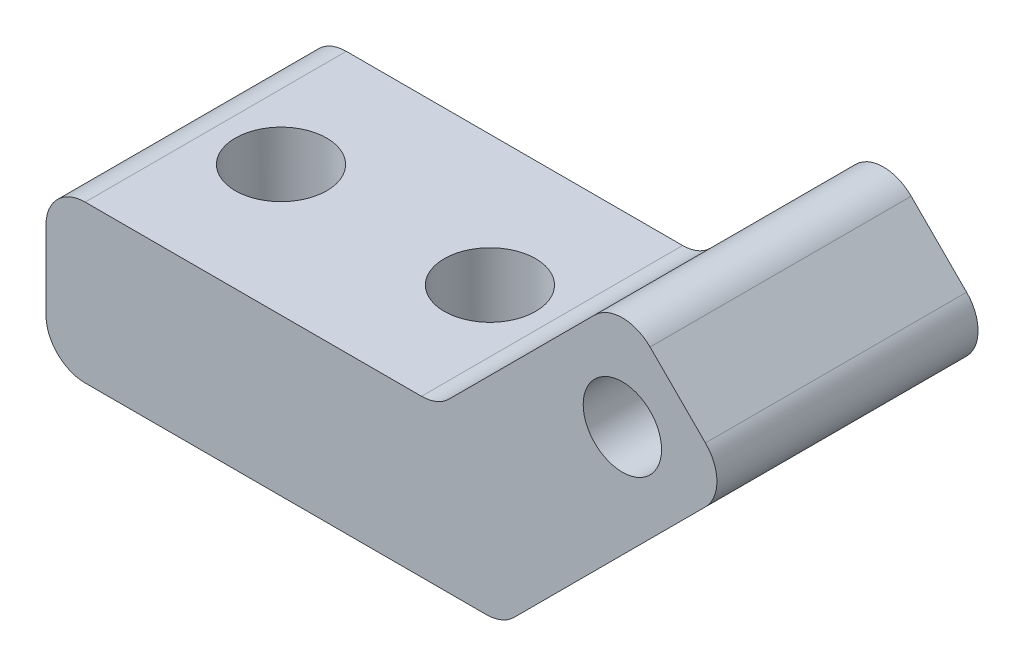
SolidWorks part; units mm, degrees
ref_plane "Front" through (0, 0, 0) normal (0, 0, 1) x (1, 0, 0)
ref_plane "Top" through (0, 0, 0) normal (0, 1, 0) x (1, 0, 0)
ref_plane "Right" through (0, 0, 0) normal (1, 0, 0) x (0, 0, -1)
sketch "Esquisse1" plane through (0, 0, 0) normal (0, 0, 1) x (1, 0, 0)
  line L1 (0, 0) -> (30, 0)
  line L2 (0, 0) -> (0, 12)
  line L3 (0, 12) -> (30, 12)
  line L4 (30, 0) -> (30, 12)
  dimension "D1" = 30
  dimension "D2" = 12
extrude "Boss.-Extru.1" add sketch "Esquisse1" along normal blind 20
sketch "Esquisse2" plane through (0, 0, 20) normal (0, 0, 1) x (1, 0, 0)
  line L0 (30, 0) -> (34.9706, 0)
  line L1 (34.9706, 0) -> (52.6274, 17.6569)
  line L2 (52.6274, 17.6569) -> (44.1421, 26.1421)
  line L3 (44.1421, 26.1421) -> (30, 12)
  line L4 (30, 12) -> (30, 0)
  line L5 (30, 12) -> (0, 12) construction
  dimension "D1" = 135
  dimension "D2" = 12
  dimension "D3" = 20
extrude "Boss.-Extru.2" add sketch "Esquisse2" against normal up to vertex (20 mm away)
sketch "Esquisse3" plane through (0, 12, 0) normal (0, 1, 0) x (1, 0, 0)
  line L0 (0, -10) -> (30, -10) construction
  line L1 (0, -20) -> (0, 0) construction
  line L2 (30, -20) -> (30, 0) construction
  circle A0 centre (8, -10) radius 3.5
  circle A1 centre (24, -10) radius 3.5
  dimension "D1" = 16
  dimension "D2" = 8
  dimension "D3" = 7
extrude "Enlèv. mat.-Extru.1" cut sketch "Esquisse3" against normal through all both and the other way through all
sketch "Esquisse4" plane through (0, 0, 20) normal (0, 0, 1) x (1, 0, 0)
  line L0 (48.3848, 21.8995) -> (44.1421, 17.6569) construction
  line L1 (52.6274, 17.6569) -> (44.1421, 26.1421) construction
  circle A0 centre (44.1421, 17.6569) radius 3
  dimension "D1" = 6
  dimension "D2" = 6
extrude "Enlèv. mat.-Extru.2" cut sketch "Esquisse4" against normal through all both and the other way through all
fillet "Congé1" radius 3 6 edges at (52.6274, 17.6569, 10) (44.1421, 26.1421, 10) (34.9706, 0, 10) (30, 12, 10) (0, 0, 10) (0, 12, 10)
